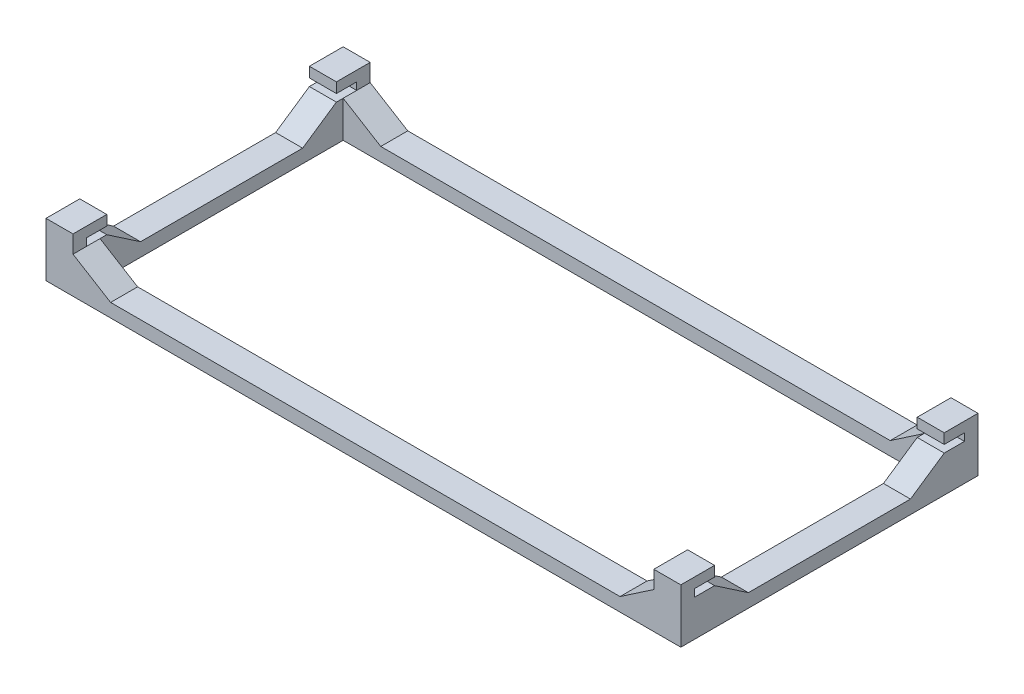
SolidWorks part; units mm, degrees
ref_plane "Спереди" through (0, 0, 0) normal (0, 0, 1) x (1, 0, 0)
ref_plane "Сверху" through (0, 0, 0) normal (0, 1, 0) x (1, 0, 0)
ref_plane "Справа" through (0, 0, 0) normal (1, 0, 0) x (0, 0, -1)
other "Configuration Table"
sketch "Эскиз1" plane through (0, 0, 0) normal (0, 1, 0) x (1, 0, 0)
  line L1 (47, -22) -> (-47, -22)
  line L2 (47, -22) -> (47, 22)
  line L3 (47, 22) -> (-47, 22)
  line L4 (-47, -22) -> (-47, 22)
  line L5 (47, -22) -> (-47, 22) construction
  line L6 (47, 22) -> (-47, -22) construction
  line L7 (43, -18) -> (-43, -18)
  line L8 (43, -18) -> (43, 18)
  line L9 (43, 18) -> (-43, 18)
  line L10 (-43, -18) -> (-43, 18)
  line L11 (43, -18) -> (-43, 18) construction
  line L12 (43, 18) -> (-43, -18) construction
  point P0 (0, 0)
  point P6 (0, 0)
  dimension "D1" = 44
  dimension "D2" = 94
  dimension "D3" = 86
  dimension "D4" = 36
extrude "Бобышка-Вытянуть2" add sketch "Эскиз1" along normal blind 2
sketch "Эскиз2" plane through (47, 0, 0) normal (1, 0, 0) x (0, 0, -1)
  line L0 (-22, 2) -> (-22, 8)
  line L1 (-22, 8) -> (-17, 8)
  line L2 (-17, 8) -> (-17, 6.5)
  line L3 (-17, 6.5) -> (-20, 6.5)
  line L4 (-20, 6.5) -> (-20, 5.4)
  line L5 (-20, 5.4) -> (-17, 5.4)
  line L6 (-17, 5.4) -> (-17, 2)
  line L7 (-22, 2) -> (22, 2) construction
  line L8 (-17, 2) -> (-22, 2)
  line L9 (-17, 5.4) -> (-12, 2)
  line L10 (-12, 2) -> (-17, 2)
  line M10 (22, 2) -> (-22, 2)
  dimension "D1" = 6
  dimension "D2" = 5
  dimension "D3" = 5
  dimension "D4" = 1.5
  dimension "D5" = 1.1
  dimension "D6" = 3
  dimension "D7" = 5
extrude "Бобышка-Вытянуть3" add sketch "Эскиз2" against normal blind 4 contours L6 L5 L4 L3 L2 L1 L0 M10 | L9 L6 M10
sketch "Эскиз3" plane through (47, 0, 0) normal (1, 0, 0) x (0, 0, -1)
  line L0 (22, 2) -> (22, 8)
  line L1 (22, 8) -> (17, 8)
  line L2 (17, 8) -> (17, 6.5)
  line L3 (17, 6.5) -> (20, 6.5)
  line L4 (20, 6.5) -> (20, 5.4)
  line L5 (20, 5.4) -> (17, 5.4)
  line L6 (17, 5.4) -> (17, 2)
  line L7 (-12, 2) -> (22, 2) construction
  line L8 (17, 2) -> (22, 2)
  line L9 (17, 5.4) -> (12, 2)
  line L10 (12, 2) -> (17, 2)
  line L11 (17, 5.4) -> (17, 2)
  line M12 (22, 2) -> (-12, 2)
  dimension "D1" = 6
  dimension "D2" = 5
  dimension "D3" = 5
  dimension "D4" = 1.5
  dimension "D5" = 1.1
  dimension "D6" = 3
  dimension "D7" = 5
extrude "Бобышка-Вытянуть4" add sketch "Эскиз3" against normal blind 4 contours L5 L6 L0 L1 L2 L3 L4 M12 | L6 L9 M12
sketch "Эскиз4" plane through (-47, 0, 0) normal (-1, 0, 0) x (0, 0, 1)
  line L0 (-22, 2) -> (-22, 8)
  line L1 (-22, 8) -> (-17, 8)
  line L2 (-17, 8) -> (-17, 6.5)
  line L3 (-17, 6.5) -> (-20, 6.5)
  line L4 (-20, 6.5) -> (-20, 5.4)
  line L5 (-20, 5.4) -> (-17, 5.4)
  line L6 (-17, 5.4) -> (-17, 2)
  line L7 (-22, 2) -> (22, 2) construction
  line L8 (-17, 2) -> (-22, 2)
  line L9 (-12, 2) -> (-17, 5.4)
  line L10 (-17, 2) -> (-12, 2)
  line M4 (22, 2) -> (-22, 2)
extrude "Бобышка-Вытянуть5" add sketch "Эскиз4" against normal blind 4 contours L6 L5 L4 L3 L2 L1 L0 M4 | L9 L6 M4
sketch "Эскиз5" plane through (-47, 0, 0) normal (-1, 0, 0) x (0, 0, 1)
  line L0 (22, 2) -> (22, 8)
  line L1 (22, 8) -> (17, 8)
  line L2 (17, 8) -> (17, 6.5)
  line L3 (17, 6.5) -> (20, 6.5)
  line L4 (20, 6.5) -> (20, 5.4)
  line L5 (20, 5.4) -> (17, 5.4)
  line L6 (17, 5.4) -> (17, 2)
  line L7 (-12, 2) -> (22, 2) construction
  line L8 (17, 2) -> (22, 2)
  line L9 (17, 5.4) -> (12, 2)
  line L10 (12, 2) -> (17, 2)
  line M3 (22, 2) -> (-12, 2)
extrude "Бобышка-Вытянуть6" add sketch "Эскиз5" against normal blind 4 contours L6 L9 M3 | L5 L6 L0 L1 L2 L3 L4 M3
sketch "Эскиз6" plane through (0, 0, 22) normal (0, 0, 1) x (1, 0, 0)
  line L0 (-43, 2) -> (-43, 5.4)
  line L2 (-43, 5.4) -> (-37.4336, 2)
  line L3 (-43, 2) -> (43, 2) construction
  line L4 (-37.4336, 2) -> (-43, 2)
  dimension "D1" = 3.4
  dimension "D2" = 3.4
extrude "Бобышка-Вытянуть7" add sketch "Эскиз6" against normal blind 4 contours L4 L0 L2
sketch "Эскиз7" plane through (0, 0, 22) normal (0, 0, 1) x (1, 0, 0)
  line L0 (43, 2) -> (43, 5.4)
  line L1 (43, 5.4) -> (38, 2)
  line L2 (-37.4336, 2) -> (43, 2) construction
  line L3 (38, 2) -> (43, 2)
  dimension "D1" = 5
extrude "Бобышка-Вытянуть8" add sketch "Эскиз7" against normal blind 4
sketch "Эскиз8" plane through (0, 0, -22) normal (0, 0, -1) x (-1, 0, 0)
  line L0 (-43, 2) -> (-43, 5.4)
  line L1 (-43, 2) -> (-43, 8) construction
  line L2 (-43, 5.4) -> (-38, 2) construction
  line L3 (-43, 5.4) -> (-38, 2)
  line L4 (-38, 2) -> (-43, 2)
extrude "Бобышка-Вытянуть9" add sketch "Эскиз8" against normal blind 4
sketch "Эскиз9" plane through (0, 0, -22) normal (0, 0, -1) x (-1, 0, 0)
  line L0 (43, 2) -> (43, 5.4)
  line L1 (43, 2) -> (43, 8) construction
  line L2 (43, 5.4) -> (43, 0) construction
  line L3 (43, 5.4) -> (37.4336, 2)
  line L4 (37.4336, 2) -> (43, 2)
extrude "Бобышка-Вытянуть10" add sketch "Эскиз9" against normal blind 4
